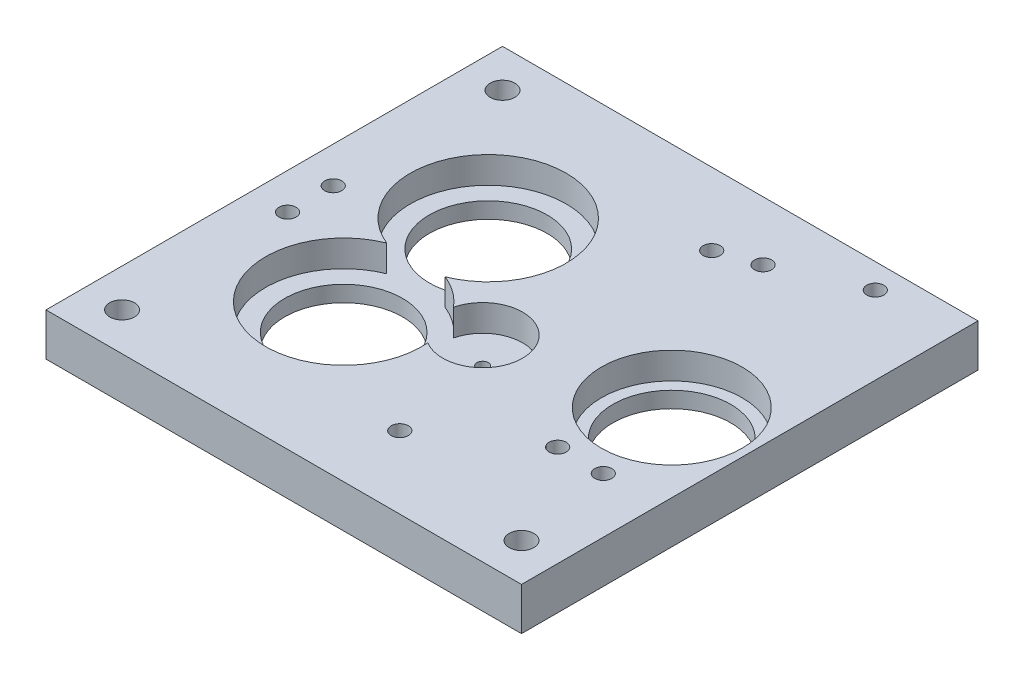
SolidWorks part; units mm, degrees
ref_plane "Front" through (0, 0, 0) normal (0, 0, 1) x (1, 0, 0)
ref_plane "Top" through (0, 0, 0) normal (0, 1, 0) x (1, 0, 0)
ref_plane "Right" through (0, 0, 0) normal (1, 0, 0) x (0, 0, -1)
sketch "Sketch1" plane through (0, 0, 0) normal (0, 1, 0) x (1, 0, 0)
  line L1 (-62.5, -60) -> (62.5, -60)
  line L2 (-62.5, -60) -> (-62.5, 60)
  line L3 (-62.5, 60) -> (62.5, 60)
  line L4 (62.5, -60) -> (62.5, 60)
  line L5 (-62.5, -60) -> (62.5, 60) construction
  line L6 (-62.5, 60) -> (62.5, -60) construction
  point P0 (0, 0)
  dimension "D1" = 125
  dimension "D2" = 120
extrude "Test_Base_Postion" add sketch "Sketch1" along normal blind 11.215
sketch "Fingers_Position" plane through (0, 11.215, 0) normal (0, 1, 0) x (1, 0, 0)
  line L0 (-62.5, 0) -> (62.5, 0) construction
  line L1 (-62.5, 60) -> (-62.5, -60) construction
  line L2 (62.5, -60) -> (62.5, 60) construction
  line L3 (-11.5, 35) -> (-11.5, 3) construction
  line L4 (-39, 35) -> (16, 35) construction
  line L5 (-39, 35) -> (-39, 3) construction
  line L6 (-39, 3) -> (16, 3) construction
  line L7 (16, 35) -> (16, 3) construction
  line L8 (16, -35) -> (-39, -35) construction
  line L9 (16, -35) -> (16, -3) construction
  line L10 (16, -3) -> (-39, -3) construction
  line L11 (-39, -35) -> (-39, -3) construction
  line L12 (-11.5, 19) -> (-39, 19) construction
  line L13 (-11.5, -3) -> (-11.5, -35) construction
  line L14 (-39, -19) -> (-11.5, -19) construction
  line L15 (-39, -19) -> (-45.25, -19) construction
  line L16 (26, 49) -> (26, -6) construction
  line L17 (26, -6) -> (58, -6) construction
  line L18 (58, -6) -> (58, 49) construction
  line L19 (58, 49) -> (26, 49) construction
  line L20 (30, 9) -> (30, -27) construction
  line L21 (30, -27) -> (54, -27) construction
  line L22 (54, -27) -> (54, 9) construction
  line L23 (54, 9) -> (30, 9) construction
  line L24 (30, -9) -> (54, -9) construction
  line L25 (42, 49) -> (42, -6) construction
  circle A0 centre (-25.25, -19) radius 20 construction
  circle A1 centre (-25.25, -19) radius 20.5 construction
  circle A2 centre (-25.25, 19) radius 20 construction
  circle A3 centre (-25.25, 19) radius 20.5 construction
  circle A4 centre (-25.25, 19) radius 19 construction
  circle A5 centre (-25.25, -19) radius 19 construction
  circle A6 centre (42, 0) radius 17.75 construction
  circle A7 centre (42, 0) radius 9 construction
  point P50 (42, 9)
  dimension "D1" = 40
  dimension "D2" = 41
  dimension "D8" = 38
  dimension "D7" = 18
  dimension "D9" = 35.5
  dimension "D3" = 55
  dimension "D4" = 32
  dimension "D5" = 55
  dimension "D6" = 32
  dimension "D10" = 24
  dimension "D11" = 32
  dimension "D12" = 55
  dimension "D13" = 40
  dimension "D14" = 20.5
  dimension "D15" = 10
sketch "Thumb_Position" plane through (0, 11.215, 0) normal (0, 1, 0) x (1, 0, 0)
  line L0 (42, 49) -> (42, -6) construction
  line L1 (58, -6) -> (26, -6) construction
  line L2 (58, -6) -> (58, 49) construction
  line L3 (58, 49) -> (26, 49) construction
  line L4 (26, -6) -> (26, 49) construction
  line L5 (30, -9) -> (54, -9) construction
  line L6 (54, -27) -> (30, -27) construction
  line L7 (54, -27) -> (54, 9) construction
  line L8 (54, 9) -> (30, 9) construction
  line L9 (30, -27) -> (30, 9) construction
  line L10 (42, 9) -> (42, -9) construction
  line L11 (62.5, -60) -> (62.5, 60) construction
  line L12 (-62.5, 0) -> (62.5, 0) construction
  circle A0 centre (42, 0) radius 17.75 construction
  circle A1 centre (42, 0) radius 9 construction
  dimension "D1" = 18
  dimension "D2" = 35.5
  dimension "D3" = 24
  dimension "D4" = 36
  dimension "D5" = 55
  dimension "D6" = 32
  dimension "D7" = 20.5
  dimension "D8" = 40
sketch "Intermediate_Gear_Position" plane through (0, 11.215, 0) normal (0, 1, 0) x (1, 0, 0)
  line L0 (-38, -12) -> (-38, 12) construction
  line L1 (-20, 12) -> (-20, -12) construction
  line L2 (-20, 12) -> (-56, 12) construction
  line L3 (-56, 12) -> (-56, -12) construction
  line L4 (-20, -12) -> (-56, -12) construction
  line L5 (-38, 0) -> (-20, 0) construction
  line L7 (-62.5, 0) -> (62.5, 0) construction
  line L10 (16, 35) -> (16, 3) construction
  circle A3 centre (0.6461, -8.3515) radius 18 construction
  circle A6 centre (-29, 0) radius 12.8 construction
  circle A7 centre (0.6461, -8.3515) radius 9 construction
  circle A8 centre (-25.25, -19) radius 19 construction
  dimension "D3" = 36
  dimension "D6" = 36
  dimension "D10" = 18
  dimension "D11" = 25.6
  dimension "D1" = 24
  dimension "D2" = 36
sketch "Sketch8" plane through (0, 11.215, 0) normal (0, 1, 0) x (1, 0, 0)
  circle A0 centre (-25.25, 19) radius 20.5
  circle A1 centre (-25.25, -19) radius 20.5
  dimension "D1" = 41
extrude "Finger_Gears" cut sketch "Sketch8" against normal blind 7 contours A1 A0 | A0 A1 | A0 A1
sketch "Sketch9" plane through (0, 11.215, 0) normal (0, 1, 0) x (1, 0, 0)
  circle A0 centre (0.6461, -8.3515) radius 10.5
  dimension "D1" = 21
extrude "Intermediate_Gear" cut sketch "Sketch9" against normal blind 7
sketch "Sketch11" plane through (0, 11.215, 0) normal (0, 1, 0) x (1, 0, 0)
  circle A0 centre (42, 0) radius 18.5
  dimension "D1" = 37
extrude "XL320_Finger_Knuckle_Mount" cut sketch "Sketch11" against normal blind 7
sketch "Sketch10" plane through (0, 11.215, 0) normal (0, 1, 0) x (1, 0, 0)
  circle A0 centre (-25.25, 19) radius 15.5
  circle A1 centre (-25.25, -19) radius 15.5
  circle A2 centre (42, 0) radius 15.5
  dimension "D1" = 31
extrude "Connect_Finger_Holes" cut sketch "Sketch10" against normal through all
sketch "Thumb_Mount_Holes" plane through (0, 11.215, 0) normal (0, 1, 0) x (1, 0, 0)
  line L0 (42, 49) -> (42, 53.5) construction
  line L1 (58, 49) -> (26, 49) construction
  line L2 (26, 49) -> (21.5, 49) construction
  line L3 (21.5, 49) -> (21.5, 44.5) construction
  line L4 (42, -27) -> (42, -9) construction
  line L5 (54, -27) -> (30, -27) construction
  line L6 (48, -27) -> (48, -24) construction
  line L7 (48, -24) -> (54, -24) construction
  line L8 (54, -27) -> (54, 9) construction
  circle A0 centre (21.5, 44.5) radius 2.25
  circle A1 centre (42, 53.5) radius 2.25
  circle A2 centre (48, -24) radius 2.25
  circle A3 centre (36, -24) radius 2.25
  dimension "D3" = 4.5
  dimension "D5" = 4.5
  dimension "D1" = 6
  dimension "D2" = 3
  dimension "D4" = 4.5
extrude "Thumb_Mount_Holes_(M4)" cut sketch "Thumb_Mount_Holes" against normal through all
sketch "Sketch16" plane through (0, 11.215, 0) normal (0, 1, 0) x (1, 0, 0)
  line L0 (-62.5, 0) -> (62.5, 0) construction
  line L1 (-62.5, 60) -> (-62.5, -60) construction
  line L2 (16, 35) -> (16, 41) construction
  line L3 (16, 41) -> (11.5, 41) construction
  line L4 (-53, 12) -> (-53, 6) construction
  line L5 (-20, 12) -> (-56, 12) construction
  line L6 (-53, 6) -> (-56, 6) construction
  line L7 (-56, 12) -> (-56, -12) construction
  circle A0 centre (11.5, 41) radius 2.25
  circle A1 centre (11.5, -41) radius 2.25
  circle A2 centre (-53, 6) radius 2.25
  circle A4 centre (-53, -6) radius 2.25
  dimension "D2" = 4.5
  dimension "D4" = 4.5
  dimension "D1" = 6
  dimension "D3" = 4.5
  dimension "D5" = 6
  dimension "D6" = 3
extrude "Fingers_Mount_Holes_(M4)" cut sketch "Sketch16" against normal through all
sketch "Sketch17" plane through (0, 11.215, 0) normal (0, 1, 0) x (1, 0, 0)
  line L0 (-62.5, 50) -> (-52.5, 50) construction
  line L1 (-62.5, 60) -> (-62.5, -60) construction
  line L2 (62.5, 60) -> (-62.5, 60) construction
  line L3 (-62.5, 0) -> (62.5, 0) construction
  line L4 (0, 0) -> (0, -60) construction
  line L5 (-62.5, -60) -> (62.5, -60) construction
  circle A0 centre (-52.5, 50) radius 3.25
  circle A1 centre (-52.5, -50) radius 3.25
  circle A2 centre (52.5, -50) radius 3.25
  dimension "D3" = 6.5
  dimension "D1" = 10
  dimension "D2" = 10
extrude "Connect_Holes_(M6)" cut sketch "Sketch17" against normal through all
sketch "Sketch18" plane through (0, 0, 0) normal (0, -1, 0) x (1, 0, 0)
  line L0 (11.5, 41) -> (11.5, 47.6395) construction
  line L1 (11.5, 47.6395) -> (5.75, 44.3198)
  line L2 (5.75, 44.3198) -> (11.5, 41) construction
  line L3 (11.5, 41) -> (5.75, 37.6802) construction
  line L4 (5.75, 37.6802) -> (11.5, 34.3605)
  line L5 (11.5, 34.3605) -> (11.5, 41) construction
  line L6 (11.5, 41) -> (17.25, 37.6802) construction
  line L7 (17.25, 37.6802) -> (17.25, 44.3198)
  line L8 (17.25, 44.3198) -> (11.5, 41) construction
  line L9 (11.5, 47.6395) -> (17.25, 44.3198)
  line L10 (5.75, 44.3198) -> (5.75, 37.6802)
  line L11 (11.5, 34.3605) -> (17.25, 37.6802)
  line L12 (11.5, -34.3605) -> (5.75, -37.6802)
  line L13 (5.75, -37.6802) -> (5.75, -44.3198)
  line L14 (11.5, -41) -> (11.5, -34.3605) construction
  line L15 (17.25, -44.3198) -> (17.25, -37.6802)
  line L16 (17.25, -37.6802) -> (11.5, -41) construction
  line L17 (11.5, -41) -> (17.25, -44.3198) construction
  line L18 (11.5, -47.6395) -> (17.25, -44.3198)
  line L19 (5.75, -44.3198) -> (11.5, -47.6395)
  line L20 (11.5, -34.3605) -> (17.25, -37.6802)
  line L21 (5.75, -37.6802) -> (11.5, -41) construction
  line L22 (11.5, -47.6395) -> (11.5, -41) construction
  line L23 (11.5, -41) -> (5.75, -44.3198) construction
  line L24 (15.75, -41.1802) -> (15.75, -47.8198)
  line L25 (27.25, -47.8198) -> (27.25, -41.1802)
  line L26 (21.5, -51.1395) -> (21.5, -44.5) construction
  line L27 (21.5, -44.5) -> (15.75, -47.8198) construction
  line L28 (21.5, -51.1395) -> (27.25, -47.8198)
  line L29 (15.75, -47.8198) -> (21.5, -51.1395)
  line L30 (15.75, -41.1802) -> (21.5, -44.5) construction
  line L31 (21.5, -44.5) -> (27.25, -47.8198) construction
  line L32 (21.5, -37.8605) -> (27.25, -41.1802)
  line L33 (21.5, -37.8605) -> (15.75, -41.1802)
  line L34 (21.5, -44.5) -> (21.5, -37.8605) construction
  line L35 (27.25, -41.1802) -> (21.5, -44.5) construction
  line L36 (42, -60.1395) -> (47.75, -56.8198)
  line L37 (42, -60.1395) -> (42, -53.5) construction
  line L38 (36.25, -56.8198) -> (42, -60.1395)
  line L39 (42, -46.8605) -> (36.25, -50.1802)
  line L40 (47.75, -50.1802) -> (42, -53.5) construction
  line L41 (36.25, -50.1802) -> (42, -53.5) construction
  line L42 (42, -46.8605) -> (47.75, -50.1802)
  line L43 (42, -53.5) -> (47.75, -56.8198) construction
  line L44 (47.75, -56.8198) -> (47.75, -50.1802)
  line L45 (36.25, -50.1802) -> (36.25, -56.8198)
  line L46 (42, -53.5) -> (42, -46.8605) construction
  line L47 (42, -53.5) -> (36.25, -56.8198) construction
  circle A0 centre (11.5, 41) radius 5.75 construction
  circle A1 centre (11.5, -41) radius 5.75 construction
  circle A2 centre (21.5, -44.5) radius 5.75 construction
  circle A3 centre (42, -53.5) radius 5.75 construction
  point P9 (11.5, 46.75)
  point P37 (44.25, -51.481)
  point P38 (0, 0)
  point P39 (11.5, -35.25)
  point P40 (21.5, -38.75)
  point P41 (42, -47.75)
  circle M5 centre (11.5, -41) radius 2.25
  circle M6 centre (11.5, 41) radius 2.25
  circle M7 centre (21.5, -44.5) radius 2.25
  circle M8 centre (42, -53.5) radius 2.25
  dimension "D1" = 11.5
  dimension "D2" = 60
  dimension "D3" = 60
  dimension "D6" = 60
  dimension "D7" = 60
  dimension "D9" = 60
  dimension "D10" = 60
  dimension "D12" = 60
  dimension "D13" = 60
extrude "Nuts_(M4)" cut sketch "Sketch18" against normal blind 4 contours A0 M6 | A3 M8 | A1 A2 | L33 L15 L20 L12 L13 L19 L18 L24 M5 | L32 L33 L15 L18 L24 L29 L28 L25 M7 | L15 L33 L24 L18
sketch "Sketch19" plane through (0, 0, 0) normal (0, -1, 0) x (1, 0, 0)
  line L0 (-52.5, 50) -> (-52.5, 58.3716) construction
  line L1 (-52.5, 50) -> (-59.75, 54.1858) construction
  line L2 (-52.5, 50) -> (-45.25, 54.1858) construction
  line L3 (-52.5, 50) -> (-59.75, 45.8142) construction
  line L4 (-52.5, 50) -> (-45.25, 45.8142) construction
  line L5 (-52.5, 50) -> (-52.5, 41.6284) construction
  line L6 (-52.5, 58.3716) -> (-59.75, 54.1858)
  line L7 (-59.75, 54.1858) -> (-59.75, 45.8142)
  line L8 (-59.75, 45.8142) -> (-52.5, 41.6284)
  line L9 (-52.5, 41.6284) -> (-45.25, 45.8142)
  line L10 (-45.25, 45.8142) -> (-45.25, 54.1858)
  line L11 (-45.25, 54.1858) -> (-52.5, 58.3716)
  line L12 (52.5, 50) -> (52.5, 58.3716) construction
  line L13 (52.5, 50) -> (45.25, 54.1858) construction
  line L14 (52.5, 50) -> (45.25, 45.8142) construction
  line L15 (52.5, 50) -> (52.5, 41.6284) construction
  line L16 (52.5, 50) -> (59.75, 54.1858) construction
  line L17 (52.5, 50) -> (59.75, 45.8142) construction
  line L18 (52.5, 58.3716) -> (45.25, 54.1858)
  line L19 (45.25, 54.1858) -> (45.25, 45.8142)
  line L20 (45.25, 45.8142) -> (52.5, 41.6284)
  line L21 (52.5, 41.6284) -> (59.75, 45.8142)
  line L22 (59.75, 45.8142) -> (59.75, 54.1858)
  line L23 (59.75, 54.1858) -> (52.5, 58.3716)
  line L24 (-52.5, -50) -> (-52.5, -41.6284) construction
  line L25 (-52.5, -50) -> (-59.75, -45.8142) construction
  line L26 (-52.5, -50) -> (-59.75, -54.1858) construction
  line L27 (-52.5, -50) -> (-52.5, -58.3716) construction
  line L28 (-52.5, -50) -> (-45.25, -54.1858) construction
  line L29 (-52.5, -50) -> (-45.25, -45.8142) construction
  line L30 (-52.5, -41.6284) -> (-59.75, -45.8142)
  line L31 (-59.75, -45.8142) -> (-59.75, -54.1858)
  line L32 (-59.75, -54.1858) -> (-52.5, -58.3716)
  line L33 (-52.5, -58.3716) -> (-45.25, -54.1858)
  line L34 (-45.25, -54.1858) -> (-45.25, -45.8142)
  line L35 (-45.25, -45.8142) -> (-52.5, -41.6284)
  circle A0 centre (-52.5, 50) radius 7.25 construction
  circle A1 centre (52.5, 50) radius 7.25 construction
  circle A2 centre (-52.5, -50) radius 7.25 construction
  point P27 (-52.5, 57.25)
  point P28 (52.5, 57.25)
  point P29 (-52.5, -42.75)
  dimension "D1" = 14.5
  dimension "D3" = 60
  dimension "D4" = 60
  dimension "D6" = 60
  dimension "D7" = 60
  dimension "D9" = 60
  dimension "D10" = 60
extrude "Nuts_(M6)" cut sketch "Sketch19" against normal blind 6
sketch "Sketch21" plane through (0, 4.215, 0) normal (0, 1, 0) x (1, 0, 0)
  circle A0 centre (0.6461, -8.3515) radius 1.5
  dimension "D1" = 3
extrude "Fix_Gear_Rod_Hole" cut sketch "Sketch21" against normal blind 2.5
